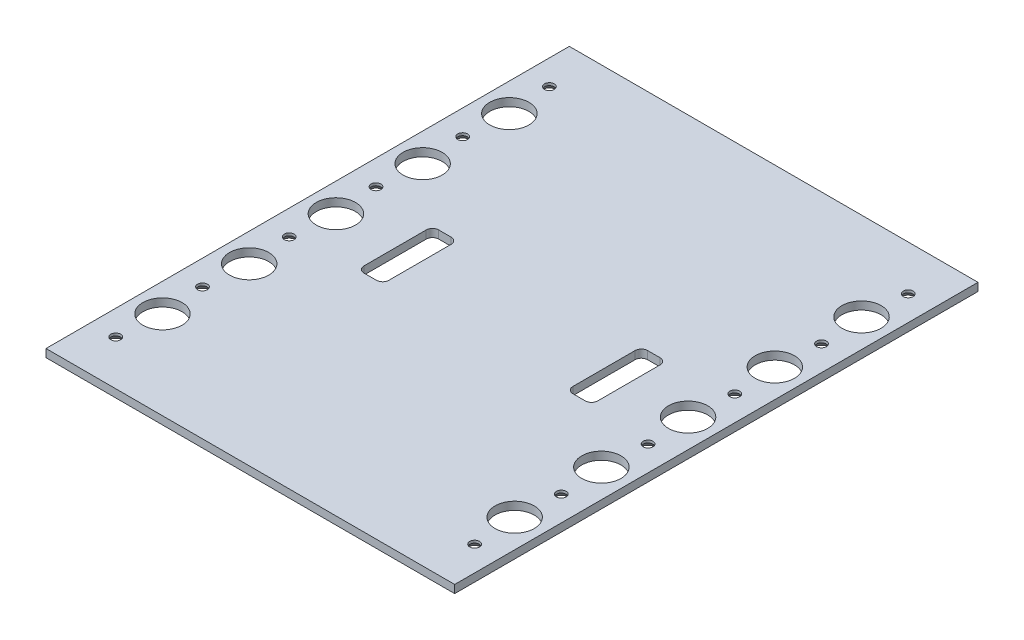
SolidWorks part; units mm, degrees
material "6061-T6 (SS)"
ref_plane "Front Plane" through (0, 0, 0) normal (0, 0, 1) x (1, 0, 0)
ref_plane "Top Plane" through (0, 0, 0) normal (0, 1, 0) x (1, 0, 0)
ref_plane "Right Plane" through (0, 0, 0) normal (1, 0, 0) x (0, 0, -1)
sketch "Sketch1" plane through (0, 0, 0) normal (0, 1, 0) x (1, 0, 0)
  line L1 (-104.14, 133.35) -> (104.14, 133.35)
  line L2 (-104.14, 133.35) -> (-104.14, -133.35)
  line L3 (-104.14, -133.35) -> (104.14, -133.35)
  line L4 (104.14, 133.35) -> (104.14, -133.35)
  line L5 (-104.14, 133.35) -> (104.14, -133.35) construction
  line L6 (-104.14, -133.35) -> (104.14, 133.35) construction
  point P0 (0, 0)
  dimension "D1" = 208.28
  dimension "D2" = 266.7
extrude "Boss-Extrude1" add sketch "Sketch1" along normal blind 4.064
sketch "Sketch2" plane through (0, 4.064, 0) normal (0, 1, 0) x (1, 0, 0)
  line L0 (-104.14, 133.35) -> (-104.14, -133.35) construction
  line L1 (-59.5765, 19.05) -> (-46.8765, 19.05)
  line L2 (-59.5765, 19.05) -> (-59.5765, -19.05)
  line L3 (-59.5765, -19.05) -> (-46.8765, -19.05)
  line L4 (-46.8765, 19.05) -> (-46.8765, -19.05)
  line L5 (-59.5765, 19.05) -> (-46.8765, -19.05) construction
  line L6 (-59.5765, -19.05) -> (-46.8765, 19.05) construction
  point P0 (-53.2265, 0)
  point P7 (0, 0)
  dimension "D1" = 50.9135
  dimension "D2" = 12.7
  dimension "D3" = 38.1
extrude "Cut-Extrude1" cut sketch "Sketch2" against normal through all
mirror "Mirror1" about plane through (0, 0, 0) normal (1, 0, 0) of "Cut-Extrude1"
fillet "Fillet1" radius 3.175 8 edges at (59.5765, 2.032, 19.05) (46.8765, 2.032, 19.05) (59.5765, 2.032, -19.05) (46.8765, 2.032, -19.05) (-46.8765, 2.032, 19.05) (-59.5765, 2.032, 19.05) (-46.8765, 2.032, -19.05) (-59.5765, 2.032, -19.05)
sketch "Sketch3" plane through (0, 0, 0) normal (0, 1, 0) x (1, 0, 0)
  line L0 (-104.14, 133.35) -> (-104.14, -133.35) construction
  line L1 (104.14, 133.35) -> (-104.14, 133.35) construction
  line L3 (104.14, 0) -> (-104.14, 0) construction
  line L4 (104.14, -133.35) -> (104.14, 133.35) construction
  line L5 (-91.44, 66.294) -> (-89.74, 88.392) construction
  line L6 (-89.74, 88.392) -> (-91.44, 110.49) construction
  circle A0 centre (-89.74, 88.392) radius 10
  circle A1 centre (-89.74, 44.196) radius 10
  circle A2 centre (-89.74, 0) radius 10
  circle A3 centre (-89.74, -44.196) radius 10
  circle A9 centre (-91.44, 110.49) radius 6.35 construction
  circle A11 centre (-91.44, -110.49) radius 6.35 construction
  circle A12 centre (-91.44, -66.294) radius 6.35 construction
  circle A13 centre (-91.44, -22.098) radius 6.35 construction
  circle A14 centre (-91.44, 22.098) radius 6.35 construction
  circle A15 centre (-91.44, 66.294) radius 6.35 construction
  circle A16 centre (-89.74, -88.392) radius 10
  dimension "D1" = 20
  dimension "D2" = 14.4
  dimension "D7" = 12.7
  dimension "D5" = 44.196
  dimension "D6" = 12.7
  dimension "D8" = 22.86
  dimension "D10" = 44.196
  dimension "D4" = 5
  dimension "D9" = 5
extrude "Cut-Extrude2" cut sketch "Sketch3" along normal through all
hole_wizard "CSK for #10 Flat Head Machine Screw2" positions "Sketch9" profile "Sketch10" countersink size "#10" standard "ANSI Inch"
sketch "Sketch9" plane through (0, 0, 0) normal (0, -1, 0) x (-1, 0, 0)
  point P0 (91.44, 110.49)
  point P3 (91.44, -110.49)
  point P7 (91.44, -66.294)
  point P10 (91.44, -22.098)
  point P13 (91.44, 22.098)
  point P16 (91.44, 66.294)
sketch "Sketch10" plane through (-91.44, 0, -110.49) normal (1, 0, 0) x (0, 0, -1)
  line L0 (0, 0) -> (0, 12.4177)
  line L1 (0, 12.4177) -> (2.4892, 10.922)
  line L2 (2.4892, 10.922) -> (2.4892, 2.7612)
  line L3 (2.4892, 2.7612) -> (4.8895, 0)
  line L5 (4.8895, 0) -> (0, 0)
  line L6 (-2.4892, 2.7612) -> (-4.8895, 0) construction
  line L10 (0, 12.4177) -> (-2.4892, 10.922) construction
  line L11 (0, -6.35) -> (0, 107.95) construction
  dimension "Hole Dia." = 4.9784
  dimension "Hole Depth" = 10.922
  dimension "Near C'Sink Dia." = 9.779
  dimension "Near C'Sink Angle" = 82
  dimension "Drill Angle" = 118
mirror "Mirror2" about plane through (0, 0, 0) normal (1, 0, 0) of "CSK for #10 Flat Head Machine Screw2", "Cut-Extrude2"
